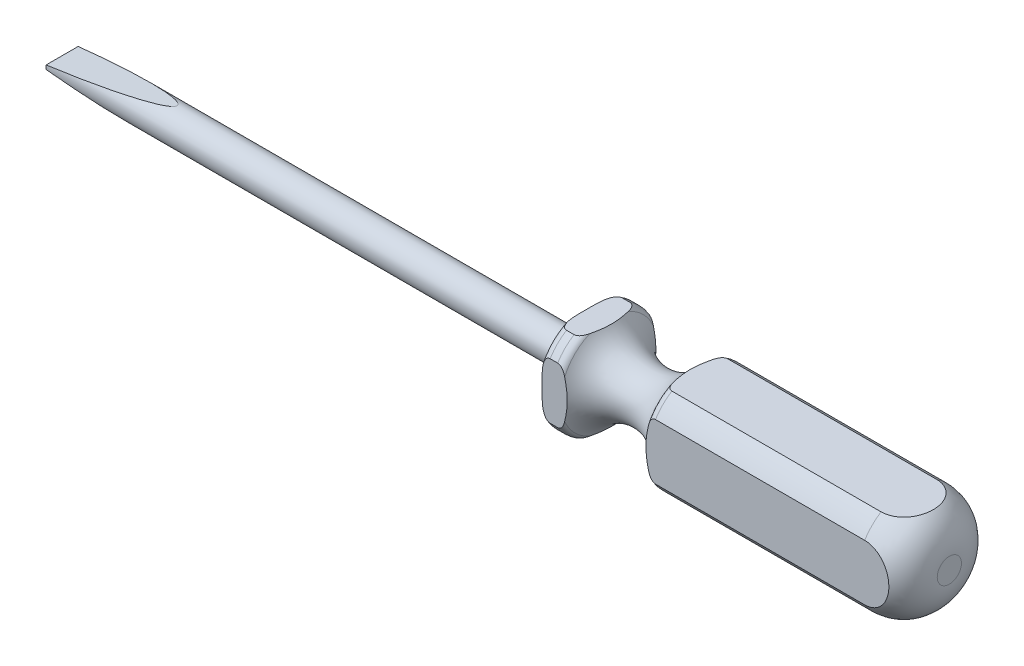
SolidWorks part; units mm, degrees
material "AISI 304"
ref_plane "Front Plane" through (0, 0, 0) normal (0, 0, 1) x (1, 0, 0)
ref_plane "Top Plane" through (0, 0, 0) normal (0, 1, 0) x (1, 0, 0)
ref_plane "Right Plane" through (0, 0, 0) normal (1, 0, 0) x (0, 0, -1)
sketch "Sketch1" plane through (0, 0, 0) normal (0, 0, 1) x (1, 0, 0)
  line L0 (-862.0518, 0) -> (42240.5378, 0) construction
  line L1 (0, 0) -> (0, 2.54)
  line L2 (0, 2.54) -> (82.55, 2.54)
  line L3 (82.55, 2.54) -> (82.55, 6.985)
  line L4 (83.82, 8.255) -> (85.011, 8.255)
  line L5 (139.7, 1.905) -> (139.7, 0)
  line L6 (100.409, 8.255) -> (133.35, 8.255)
  line L7 (0, 0) -> (139.7, 0)
  arc A0 (86.1109, 7.62) -> (99.3091, 7.62) centre (92.71, 11.43) ccw
  arc A1 (99.3091, 7.62) -> (100.409, 8.255) centre (100.409, 6.985) cw
  arc A2 (86.1109, 7.62) -> (85.011, 8.255) centre (85.011, 6.985) ccw
  arc A3 (83.82, 8.255) -> (82.55, 6.985) centre (83.82, 6.985) ccw
  arc A4 (133.35, 8.255) -> (139.7, 1.905) centre (133.35, 1.905) cw
  point P10 (0, 0)
  point P13 (95.0328, 11.43)
  point P16 (99.637, 8.255)
  dimension "D4" = 7.62
  dimension "D8" = 1.27
  dimension "D9" = 6.35
  dimension "D1" = 139.7
  dimension "D2" = 57.15
  dimension "D3" = 2.54
  dimension "D5" = 11.43
  dimension "D6" = 8.255
  dimension "D7" = 46.99
revolve "Revolve3" add sketch "Sketch1" angle 360 about L0
sketch "Sketch5" plane through (0, 0, 0) normal (0, 0, 1) x (1, 0, 0)
  line L0 (-1000, 0) -> (49000, 0) construction
  line L1 (0, -0.3175) -> (0, 0.3175)
  line L2 (0, 2.54) -> (0, -2.54) construction
  line L3 (0, 0.3175) -> (18.1008, 2.54)
  line L4 (82.55, 2.54) -> (0, 2.54) construction
  line L5 (0, -0.3175) -> (18.1008, -2.54)
  point P11 (0, 0)
  dimension "D1" = 7
  dimension "D2" = 0.3175
extrude "Cut-Extrude3" cut sketch "Sketch5" against normal through all and the other way through all
sketch "Sketch8" plane through (139.7, 0, 0) normal (1, 0, 0) x (0, 0, -1)
  line L1 (-6.985, 6.985) -> (6.985, 6.985)
  line L2 (-6.985, 6.985) -> (-6.985, -6.985)
  line L3 (-6.985, -6.985) -> (6.985, -6.985)
  line L4 (6.985, 6.985) -> (6.985, -6.985)
  line L5 (-6.985, 6.985) -> (6.985, -6.985) construction
  line L6 (-6.985, -6.985) -> (6.985, 6.985) construction
  point P0 (0, 0)
  point P5 (6.985, 0)
  point P6 (0, 6.985)
  dimension "D1" = 6.985
  dimension "D2" = 6.985
extrude "Cut-Extrude4" cut sketch "Sketch8" against normal through all flip side to cut
